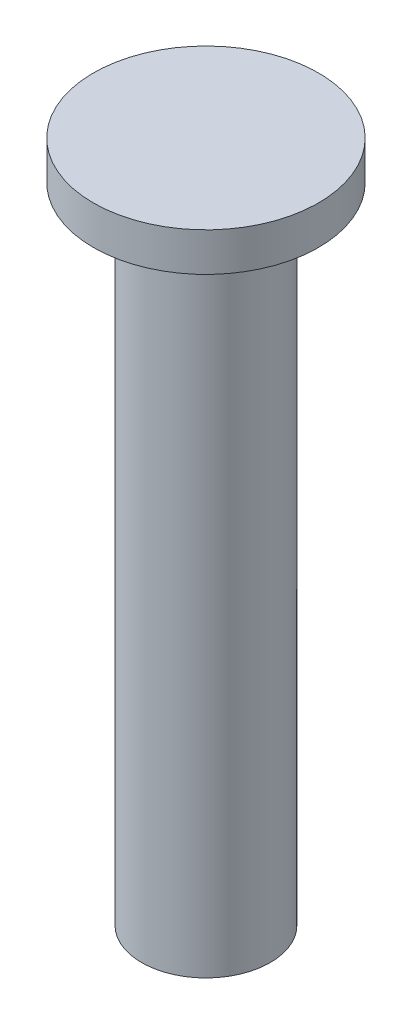
SolidWorks part; units mm, degrees
material "AISI 304"
ref_plane "前视基准面" through (0, 0, 0) normal (0, 0, 1) x (1, 0, 0)
ref_plane "上视基准面" through (0, 0, 0) normal (0, 1, 0) x (1, 0, 0)
ref_plane "右视基准面" through (0, 0, 0) normal (1, 0, 0) x (0, 0, -1)
other "Configuration Table"
sketch "草图1" plane through (0, 0, 0) normal (0, 1, 0) x (1, 0, 0)
  circle A0 centre (0, 0) radius 3.5
  dimension "D1" = 7
extrude "凸台-拉伸1" add sketch "草图1" along normal blind 1.2
sketch "草图2" plane through (0, 0, 0) normal (0, -1, 0) x (1, 0, 0)
  circle A0 centre (0, 0) radius 2
  dimension "D1" = 4
extrude "凸台-拉伸2" add sketch "草图2" along normal blind 20
